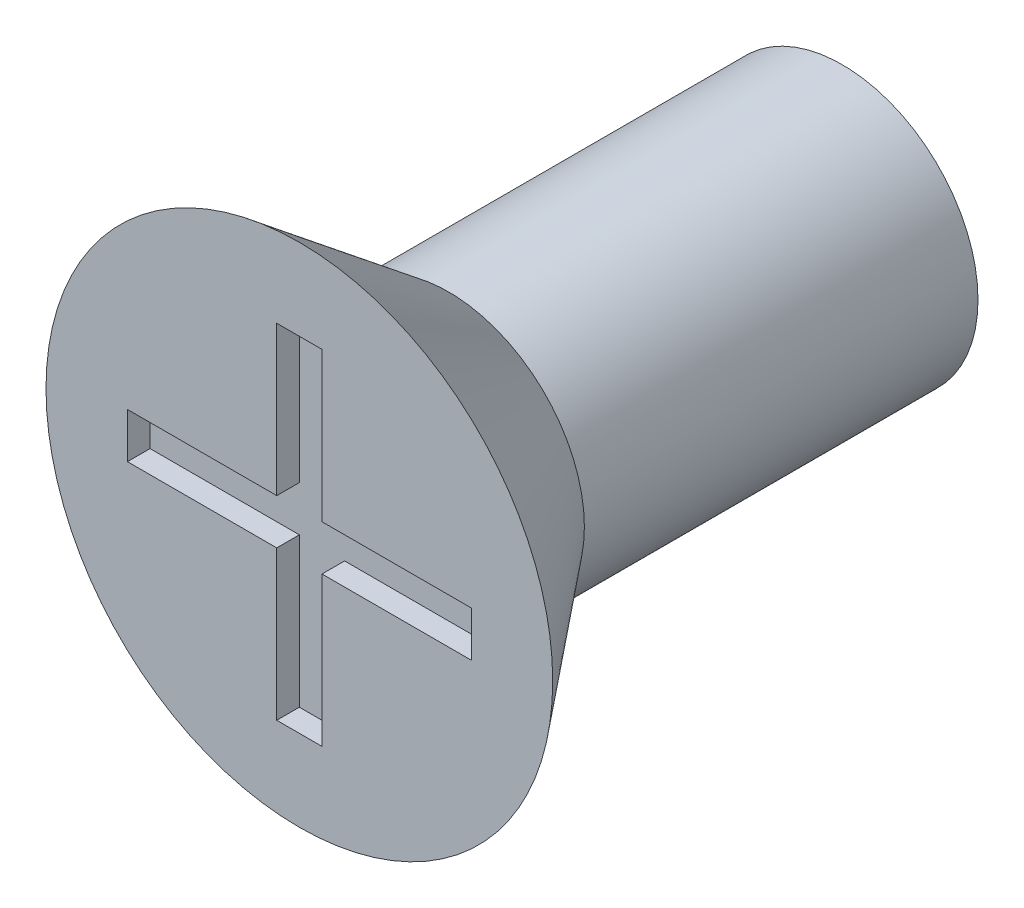
SolidWorks part; units mm, degrees
ref_plane "Front Plane" through (0, 0, 0) normal (0, 0, 1) x (1, 0, 0)
ref_plane "Top Plane" through (0, 0, 0) normal (0, 1, 0) x (1, 0, 0)
ref_plane "Right Plane" through (0, 0, 0) normal (1, 0, 0) x (0, 0, -1)
sketch "Sketch4" plane through (0, 0, 0) normal (1, 0, 0) x (0, 0, -1)
  line L0 (0, 0) -> (0, 2.8)
  line L1 (0, 0) -> (6, 0)
  line L2 (6, 0) -> (6, 1.5)
  line L3 (0, 2.8) -> (1.65, 2.8) construction
  line L4 (6, 1.5) -> (1.65, 1.5)
  line L5 (1.65, 1.5) -> (0, 2.8)
  dimension "D1" = 2.8
  dimension "D2" = 6
  dimension "D3" = 1.5
  dimension "D4" = 1.65
revolve "Revolve1" add sketch "Sketch4" angle 360 about L1
sketch "Sketch5" plane through (0, 0, 0) normal (0, 0, 1) x (1, 0, 0)
  line L2 (-1.9, -0.25) -> (1.9, -0.25)
  line L3 (-0.25, 1.9) -> (-0.25, -1.9)
  line L4 (-1.9, 0.25) -> (1.9, 0.25)
  line L5 (0.25, 1.9) -> (0.25, -1.9)
  line L6 (-0.25, 1.9) -> (0.25, 1.9)
  line L7 (1.9, 0.25) -> (1.9, -0.25)
  line L8 (0.25, -1.9) -> (-0.25, -1.9)
  line L9 (-1.9, 0.25) -> (-1.9, -0.25)
extrude "Cut-Extrude2" cut sketch "Sketch5" against normal blind 0.25
